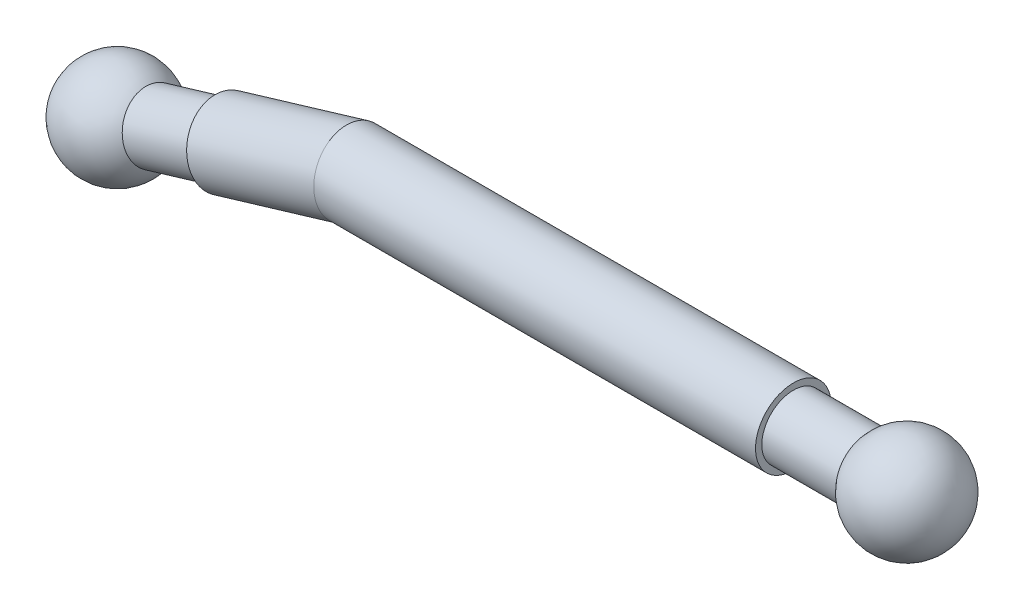
SolidWorks part; units mm, degrees
ref_plane "Front Plane" through (0, 0, 0) normal (0, 0, 1) x (1, 0, 0)
ref_plane "Top Plane" through (0, 0, 0) normal (0, 1, 0) x (1, 0, 0)
ref_plane "Right Plane" through (0, 0, 0) normal (1, 0, 0) x (0, 0, -1)
sketch "Sketch1" plane through (0, 0, 0) normal (1, 0, 0) x (0, 0, -1)
  circle A0 centre (0, 0) radius 3
  point P2 (0, 0)
  dimension "D1" = 6
sketch "Sketch2" plane through (0, 0, 0) normal (0, 0, 1) x (1, 0, 0)
  line L0 (0, 0) -> (-35, 0)
  line L1 (-35, 0) -> (-45, 0) construction
  line L2 (-45, 0) -> (-45, -3) construction
  line L3 (-35, 0) -> (-45, -3)
  dimension "D1" = 35
  dimension "D2" = 10
  dimension "D3" = 3
sweep "Sweep2" add profiles "Sketch1" path "Sketch2"
sketch "Sketch3" plane through (-42.1101, -12.633, 0) normal (-0.9578, -0.2873, 0) x (0, 0, 1)
  circle A0 centre (0, 10.0572) radius 2.5
  point P5 (0, 0)
  dimension "D1" = 5
extrude "Boss-Extrude1" add sketch "Sketch3" along normal blind 6
ref_plane "Plane1" through (-50.7305, -15.2192, 0) normal (-0.9578, -0.2873, 0) x (0, 0, 1)
sketch "Sketch4" plane through (-50.7305, -15.2192, 0) normal (-0.9578, -0.2873, 0) x (0, 0, 1)
  line L0 (0, 14.0572) -> (0, 6.0572) construction
  line L1 (0, 14.0572) -> (0, 6.0572)
  arc A0 (0, 14.0572) -> (0, 6.0572) centre (0, 10.0572) cw
  point P5 (0, 10.0572)
  dimension "D2" = 8
revolve "Revolve1" add sketch "Sketch4" angle 360 about L0
sketch "Sketch5" plane through (0, 0, 0) normal (1, 0, 0) x (0, 0, -1)
  circle A0 centre (0, 0) radius 2.5
  point P2 (0, 0)
  dimension "D1" = 5
extrude "Boss-Extrude2" add sketch "Sketch5" along normal blind 6
ref_plane "Plane2" through (9, 0, 0) normal (1, 0, 0) x (0, 0, -1)
sketch "Sketch6" plane through (9, 0, 0) normal (1, 0, 0) x (0, 0, -1)
  line L0 (0, 4) -> (0, -4)
  arc A0 (0, 4) -> (0, -4) centre (0, 0) cw
  point P5 (0, 0)
  dimension "D2" = 8
revolve "Revolve2" add sketch "Sketch6" angle 360 about L0
